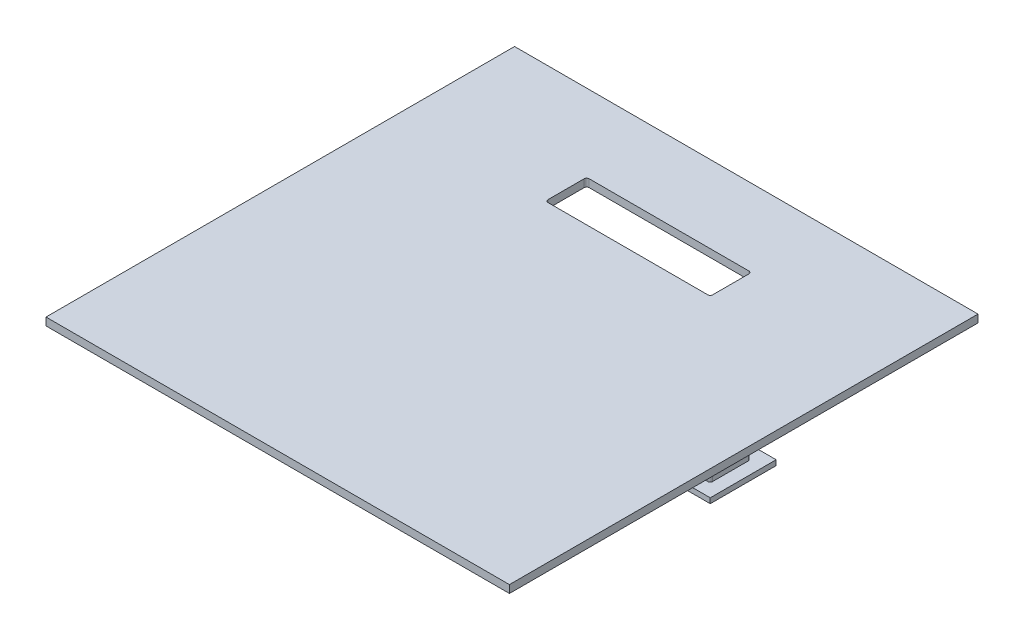
SolidWorks part; units mm, degrees
ref_plane "Alzado" through (0, 0, 0) normal (0, 0, 1) x (1, 0, 0)
ref_plane "Planta" through (0, 0, 0) normal (0, 1, 0) x (1, 0, 0)
ref_plane "Vista lateral" through (0, 0, 0) normal (1, 0, 0) x (0, 0, -1)
sketch "Croquis2" plane through (0, 0, 0) normal (0, 1, 0) x (1, 0, 0)
  line L1 (90, -91) -> (-90, -91)
  line L2 (90, -91) -> (90, 91)
  line L3 (90, 91) -> (-90, 91)
  line L4 (-90, -91) -> (-90, 91)
  line L5 (90, -91) -> (-90, 91) construction
  line L6 (90, 91) -> (-90, -91) construction
  point P0 (0, 0)
  dimension "D1" = 182
  dimension "D2" = 180
extrude "Extruir1" add sketch "Croquis2" against normal blind 3
sketch "Croquis4" plane through (0, 0, 0) normal (0, 1, 0) x (1, 0, 0)
  line L0 (90, 91) -> (-90, 91) construction
  line L1 (32, 45) -> (-32, 45)
  line L2 (32, 45) -> (32, 61)
  line L3 (32, 61) -> (-32, 61)
  line L4 (-32, 45) -> (-32, 61)
  line L5 (32, 45) -> (-32, 61) construction
  line L6 (32, 61) -> (-32, 45) construction
  point P0 (0, 53)
  dimension "D1" = 64
  dimension "D2" = 16
  dimension "D3" = 30
extrude "Extruir2" cut sketch "Croquis4" against normal blind 10
fillet "Redondeo1" radius 1 4 edges at (-32, -1.5, -45) (32, -1.5, -45) (32, -1.5, -61) (-32, -1.5, -61)
sketch "Croquis5" plane through (0, 0, 0) normal (0, 1, 0) x (1, 0, 0)
  line L8 (31.8, 46) -> (31.8, 60)
  line L9 (-31, 45.2) -> (31, 45.2)
  line L10 (-31.8, 60) -> (-31.8, 46)
  line L11 (31, 60.8) -> (-31, 60.8)
  line L12 (31.8, 46) -> (31.8, 60)
  line L13 (-31, 45.2) -> (31, 45.2)
  line L14 (-31.8, 60) -> (-31.8, 46)
  line L15 (31, 60.8) -> (-31, 60.8)
  arc A8 (31.8, 60) -> (31, 60.8) centre (31, 60) ccw
  arc A9 (31, 45.2) -> (31.8, 46) centre (31, 46) ccw
  arc A10 (-31.8, 46) -> (-31, 45.2) centre (-31, 46) ccw
  arc A11 (-31, 60.8) -> (-31.8, 60) centre (-31, 60) ccw
  arc A12 (31.8, 60) -> (31, 60.8) centre (31, 60) ccw
  arc A13 (31, 45.2) -> (31.8, 46) centre (31, 46) ccw
  arc A14 (-31.8, 46) -> (-31, 45.2) centre (-31, 46) ccw
  arc A15 (-31, 60.8) -> (-31.8, 60) centre (-31, 60) ccw
  dimension "D1" = 0.2
extrude "Extruir3" add sketch "Croquis5" against normal blind 3 separate body
sketch "Croquis7" plane through (0, -3, 0) normal (0, -1, 0) x (1, 0, 0)
  line L0 (-31, -45.2) -> (31, -45.2) construction
  line L1 (36.8, -65.8) -> (-36.8, -65.8)
  line L2 (36.8, -65.8) -> (36.8, -40.2)
  line L3 (36.8, -40.2) -> (-36.8, -40.2)
  line L4 (-36.8, -65.8) -> (-36.8, -40.2)
  line L5 (36.8, -65.8) -> (-36.8, -40.2) construction
  line L6 (36.8, -40.2) -> (-36.8, -65.8) construction
  line L7 (31, -60.8) -> (-31, -60.8) construction
  line L8 (31.8, -46) -> (31.8, -60) construction
  line L9 (-31.8, -60) -> (-31.8, -46) construction
  point P0 (0, -53)
  point P11 (-31.8, -53)
  dimension "D1" = 5
  dimension "D2" = 5
  dimension "D3" = 5
  dimension "D4" = 5
extrude "Extruir4" add sketch "Croquis7" along normal blind 2
move or copy body "Sólido-Mover/Copiar1" bodies to move or copy 104
